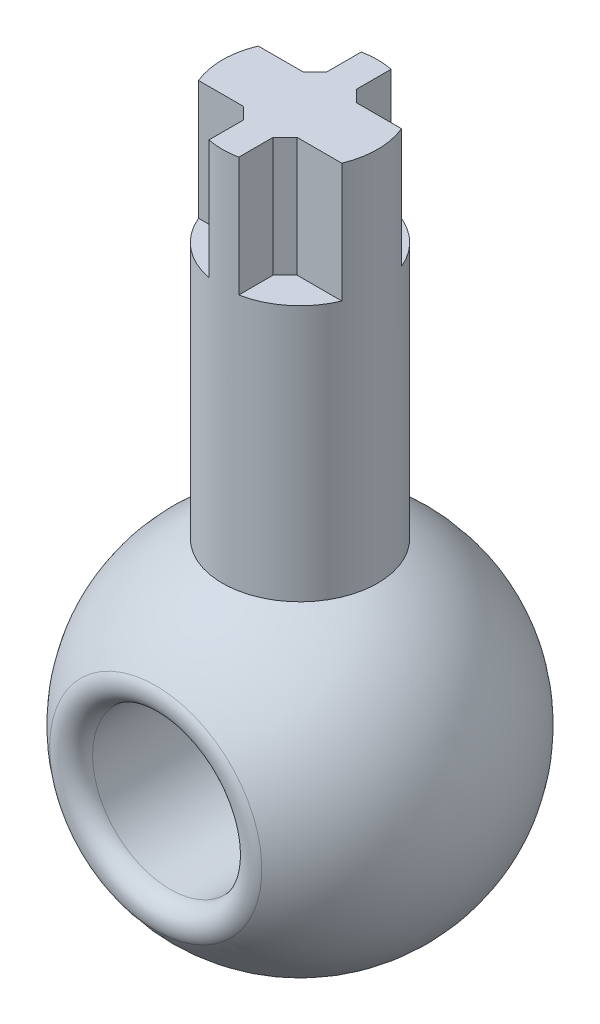
SolidWorks part; units mm, degrees
ref_plane "Plane1" through (0, 0, 0) normal (0, 0, 1) x (1, 0, 0)
ref_plane "Plane2" through (0, 0, 0) normal (0, 1, 0) x (1, 0, 0)
ref_plane "Plane3" through (0, 0, 0) normal (1, 0, 0) x (0, 0, -1)
other "Configuration Table"
sketch "s1" plane through (0, 0, 0) normal (0, 0, 1) x (1, 0, 0)
  line L0 (-56.6721, 0) -> (83.8972, 0) construction
  line L1 (-15, 0) -> (15, 0)
  arc A0 (15, 0) -> (-15, 0) centre (0, 0) ccw
  dimension "D1" = 15
revolve "1" add sketch "s1" angle 360 about L0
sketch "s2" plane through (0, 0, 0) normal (0, 1, 0) x (1, 0, 0)
  circle A0 centre (0, 0) radius 6.5
  dimension "D1" = 13
extrude "2" add sketch "s2" along normal blind 45
sketch "s3" plane through (0, 45, 0) normal (0, 1, 0) x (-1, 0, 0)
  line L0 (-10.6288, 0) -> (13.9677, 0) construction
  line L1 (56.6721, 0) -> (-83.8972, 0) construction
  line L2 (0, -10.8514) -> (0, 14.1903) construction
  line L3 (-1.25, -6.3787) -> (-1.25, -2.5)
  line L4 (1.25, -6.3787) -> (1.25, -2.5)
  line L5 (-6, 2.5) -> (-1.25, 2.5)
  line L6 (-6, -2.5) -> (-1.25, -2.5)
  line L7 (-1.25, 2.5) -> (-1.25, 6.3787)
  line L8 (1.25, 2.5) -> (1.25, 6.3787)
  line L9 (1.25, -2.5) -> (6, -2.5)
  line L10 (1.25, 2.5) -> (6, 2.5)
  circle A0 centre (0, 0) radius 6.5 construction
  arc A1 (-6, -2.5) -> (-1.25, -6.3787) centre (0, 0) ccw
  arc A2 (6, 2.5) -> (1.25, 6.3787) centre (0, 0) ccw
  arc A3 (-1.25, 6.3787) -> (-6, 2.5) centre (0, 0) ccw
  arc A4 (1.25, -6.3787) -> (6, -2.5) centre (0, 0) ccw
  dimension "D1" = 5
  dimension "D2" = 2.5
extrude "3" cut sketch "s3" against normal blind 10
chamfer "4" distance 1 angle 45 4 edges at (-1.25, 40, -2.5) (1.25, 40, -2.5) (1.25, 40, 2.5) (-1.25, 40, 2.5)
sketch "s5" plane through (0, 0, 0) normal (0, 0, 1) x (1, 0, 0)
  circle A0 centre (0, 0) radius 6.5
  dimension "D1" = 13
extrude "5" cut sketch "s5" against normal through all and the other way through all
fillet "Fillet1" radius 1.5 2 edges at (6.5, 0, -13.5185) (-6.5, 0, 13.5185)
